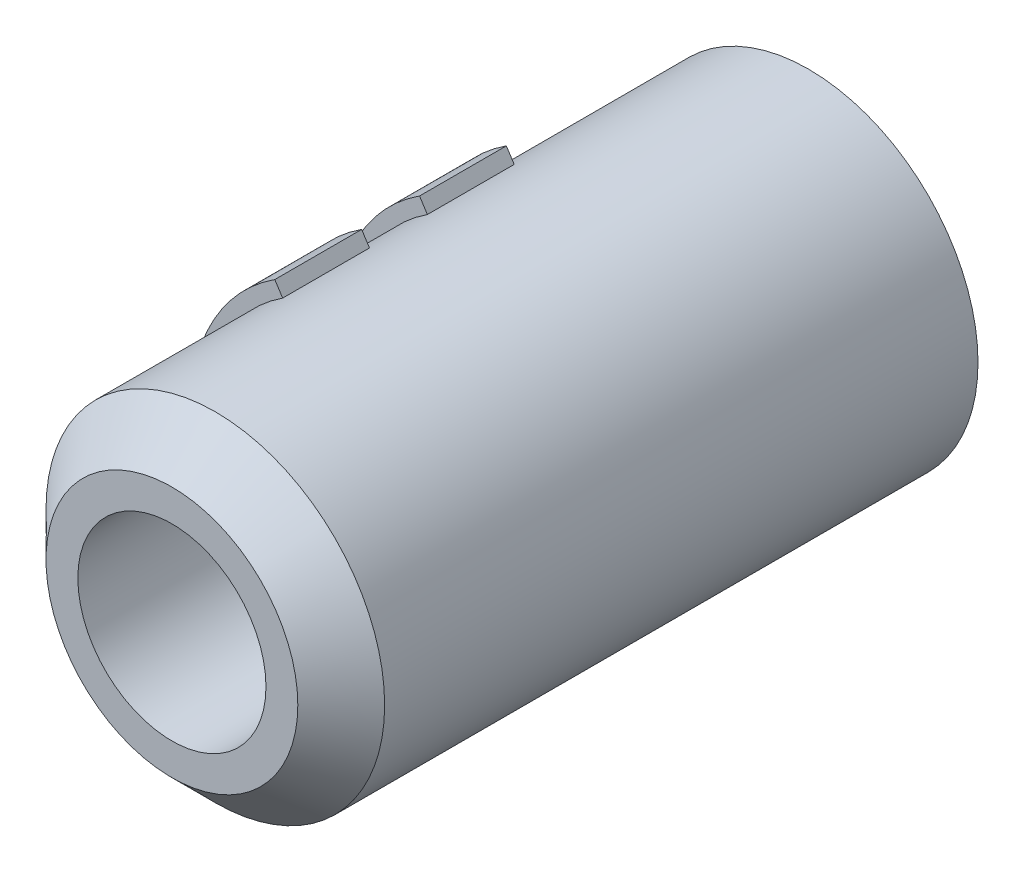
SolidWorks part; units mm, degrees
ref_plane "前视基准面" through (0, 0, 0) normal (0, 0, 1) x (1, 0, 0)
ref_plane "上视基准面" through (0, 0, 0) normal (0, 1, 0) x (1, 0, 0)
ref_plane "右视基准面" through (0, 0, 0) normal (1, 0, 0) x (0, 0, -1)
sketch "草图1" plane through (0, 0, 0) normal (0, 0, 1) x (1, 0, 0)
  circle A0 centre (0, 0) radius 5.85
  circle A1 centre (0, 0) radius 3.25
  dimension "D1" = 11.7
  dimension "D2" = 6.5
extrude "凸台-拉伸1" add sketch "草图1" along normal blind 22
chamfer "倒角1" distance 1.5 angle 45 1 edges at (5.85, 0, 22)
sketch "草图2" plane through (0, 0, 22) normal (0, 0, 1) x (1, 0, 0)
  line L0 (-3.1738, 4.9142) -> (-3.4451, 5.3342)
  line L1 (-1.2306, -5.7191) -> (-1.3358, -6.2079)
  arc A0 (-3.4451, 5.3342) -> (-1.3358, -6.2079) centre (0, 0) ccw
  circle A1 centre (0, 0) radius 5.85 construction
  arc A2 (-3.1738, 4.9142) -> (-1.2306, -5.7191) centre (0, 0) ccw
  dimension "D1" = 0.5
  dimension "D2" = 135
extrude "凸台-拉伸2" add sketch "草图2" along normal blind 3 from offset 10 offset against normal yes
sketch "草图3" plane through (0, 0, 12) normal (0, 0, -1) x (-1, 0, 0)
  line L2 (1.2306, -5.7191) -> (1.3358, -6.2079)
  line L3 (3.4451, 5.3342) -> (3.1738, 4.9142)
  line L4 (1.2306, -5.7191) -> (1.3358, -6.2079)
  line L5 (3.4451, 5.3342) -> (3.1738, 4.9142)
  arc A2 (1.2306, -5.7191) -> (3.1738, 4.9142) centre (0, 0) ccw
  arc A3 (1.3358, -6.2079) -> (3.4451, 5.3342) centre (0, 0) ccw
  arc A4 (1.2306, -5.7191) -> (3.1738, 4.9142) centre (0, 0) ccw
  arc A5 (1.3358, -6.2079) -> (3.4451, 5.3342) centre (0, 0) ccw
  dimension "D1" = 0
extrude "凸台-拉伸3" add sketch "草图3" along normal blind 3 from offset 2
